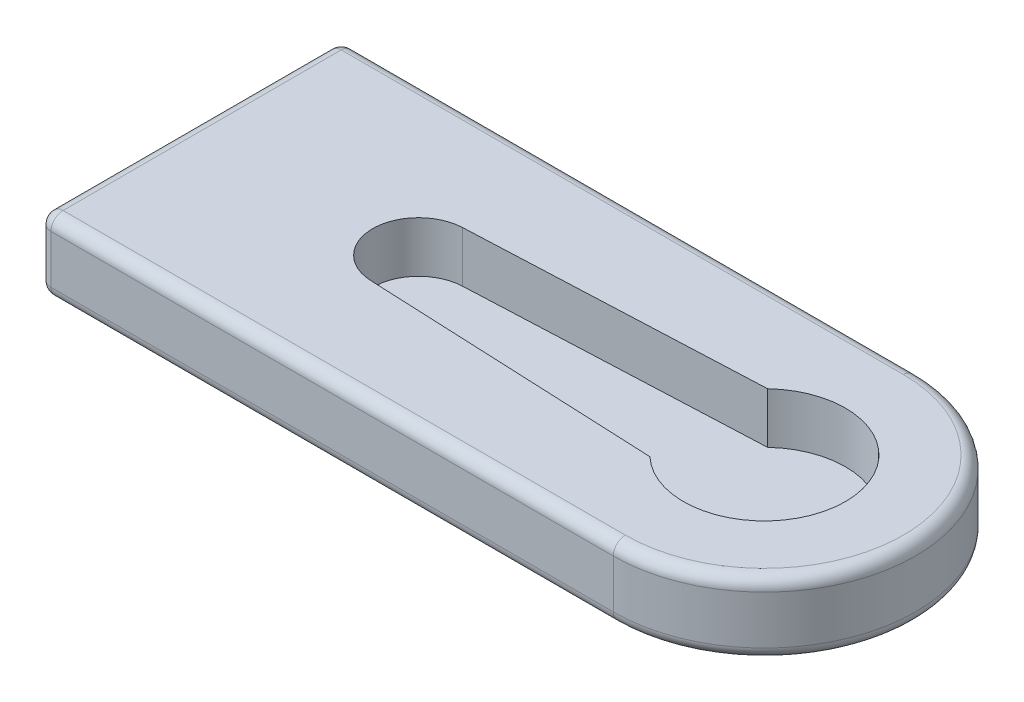
SolidWorks part; units mm, degrees
ref_plane "前视基准面" through (0, 0, 0) normal (0, 0, 1) x (1, 0, 0)
ref_plane "上视基准面" through (0, 0, 0) normal (0, 1, 0) x (1, 0, 0)
ref_plane "右视基准面" through (0, 0, 0) normal (1, 0, 0) x (0, 0, -1)
sketch "草图1" plane through (0, 0, 0) normal (0, 1, 0) x (1, 0, 0)
  line L1 (0, 0) -> (23.75, 0)
  line L2 (0, 0) -> (0, 12.5)
  line L3 (0, 12.5) -> (23.75, 12.5)
  arc A0 (23.75, 0) -> (23.75, 12.5) centre (23.75, 6.25) ccw
extrude "凸台-拉伸1" add sketch "草图1" along normal blind 3
fillet "圆角1" radius 0.5 10 edges at (11.875, 0, 0) (30, 0, -6.25) (11.875, 0, -12.5) (0, 0, -6.25) (11.875, 3, -12.5) (30, 3, -6.25) (11.875, 3, 0) (0, 3, -6.25) (0, 1.5, -12.5) (0, 1.5, 0)
sketch "草图2" plane through (0, 3, 0) normal (0, 1, 0) x (1, 0, 0)
  line L0 (0.5, 6.25) -> (30.571, 6.25) construction
  line L1 (0.5, 12) -> (0.5, 0.5) construction
  line L2 (9.3658, 8.1481) -> (21.4481, 8.6839)
  line L3 (9.3658, 4.3519) -> (21.4481, 3.8161)
  arc A0 (21.4481, 3.8161) -> (21.4481, 8.6839) centre (23.75, 6.25) ccw
  arc A1 (9.3658, 4.3519) -> (9.3658, 8.1481) centre (9.45, 6.25) cw
  dimension "D1" = 6.7
  dimension "D2" = 1.9
  dimension "D3" = 14.3
extrude "切除-拉伸1" cut sketch "草图2" against normal blind 2.1
